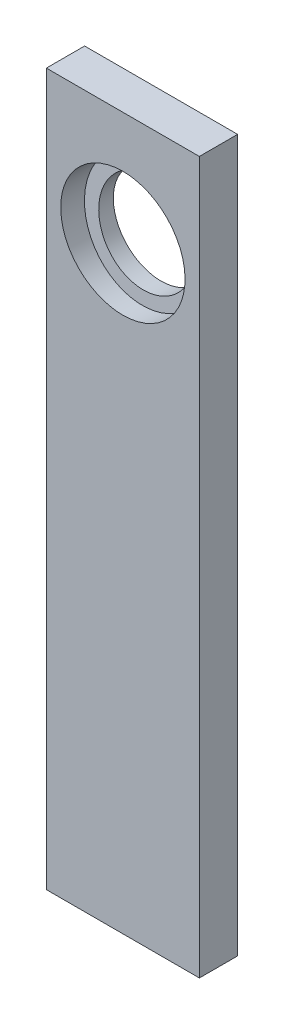
SolidWorks part; units mm, degrees
ref_plane "Front Plane" through (0, 0, 0) normal (0, 0, 1) x (1, 0, 0)
ref_plane "Top Plane" through (0, 0, 0) normal (0, 1, 0) x (1, 0, 0)
ref_plane "Right Plane" through (0, 0, 0) normal (1, 0, 0) x (0, 0, -1)
sketch "Sketch1" plane through (0, 0, 0) normal (0, 0, 1) x (1, 0, 0)
  line L1 (-40, 186) -> (40, 186)
  line L2 (-40, 186) -> (-40, -186)
  line L3 (-40, -186) -> (40, -186)
  line L4 (40, 186) -> (40, -186)
  line L5 (-40, 186) -> (40, -186) construction
  line L6 (-40, -186) -> (40, 186) construction
  point P0 (0, 0)
  dimension "D1" = 372
  dimension "D2" = 80
extrude "Boss-Extrude1" add sketch "Sketch1" along normal blind 20
sketch "Sketch2" plane through (0, 0, 20) normal (0, 0, 1) x (1, 0, 0)
  line L0 (0, -186) -> (0, 126)
  line L1 (-40, -186) -> (40, -186) construction
  dimension "D1" = 312
ref_plane "Plane1" through (0, 126, 0) normal (0, 1, 0) x (1, 0, 0)
sketch "Sketch3" plane through (0, 126, 0) normal (0, 1, 0) x (1, 0, 0)
  line L0 (0, -20) -> (0, 0)
  line L2 (0, -7.5) -> (15.3391, -7.5) construction
ref_plane "Plane3" through (0, 1.135, 16.2314) normal (0, -0.0698, -0.9976) x (1, 0, 0)
sketch "Sketch4" plane through (0, 1.135, 16.2314) normal (0, -0.0698, -0.9976) x (1, 0, 0)
  line L0 (0, -124.2979) -> (0, -125.6931) construction
  circle A0 centre (0, -124.9955) radius 32.5
  dimension "D1" = 65
extrude "Cut-Extrude2" cut sketch "Sketch4" against normal through all
sketch "Sketch5" plane through (0, 1.135, 16.2314) normal (0, 0.0698, 0.9976) x (1, 0, 0)
  circle A0 centre (0, 124.2979) radius 25
  dimension "D1" = 50
extrude "Cut-Extrude3" cut sketch "Sketch5" against normal through all
